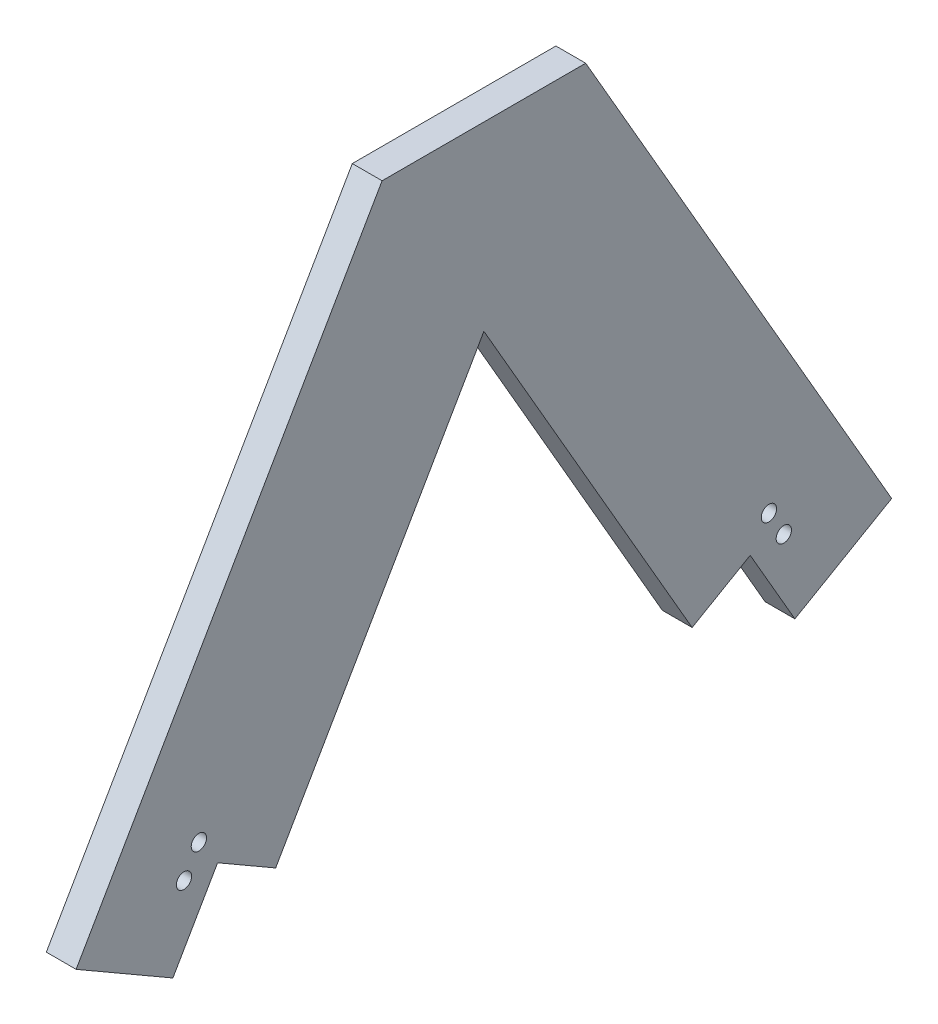
SolidWorks part; units mm, degrees
ref_plane "Front Plane" through (0, 0, 0) normal (0, 0, 1) x (1, 0, 0)
ref_plane "Top Plane" through (0, 0, 0) normal (0, 1, 0) x (1, 0, 0)
ref_plane "Right Plane" through (0, 0, 0) normal (1, 0, 0) x (0, 0, -1)
sketch "Sketch1" plane through (0, 0, 0) normal (1, 0, 0) x (0, 0, -1)
  line L0 (0, 0) -> (76.2, 131.9823)
  line L1 (119.5861, 131.9823) -> (195.7861, 0)
  line L2 (0, 0) -> (43.9941, 0)
  line L3 (43.9941, 0) -> (97.893, 93.3557)
  line L4 (97.893, 93.3557) -> (151.792, 0)
  line L5 (151.792, 0) -> (195.7861, 0)
  line L6 (76.2, 131.9823) -> (119.5861, 131.9823)
  dimension "D1" = 152.4
  dimension "D2" = 152.4
  dimension "D3" = 38.1
  dimension "D4" = 38.1
  dimension "D5" = 60
extrude "Boss-Extrude1" add sketch "Sketch1" along normal blind 6.35
sketch "Sketch2" plane through (6.35, 0, 0) normal (1, 0, 0) x (0, 0, -1)
  line L0 (43.9941, 0) -> (10.9985, 19.05)
  line L1 (76.2, 131.9823) -> (0, 0) construction
  line L2 (10.9985, 19.05) -> (0, 0)
  line L3 (0, 0) -> (43.9941, 0)
extrude "Cut-Extrude1" cut sketch "Sketch2" against normal through all
sketch "Sketch3" plane through (6.35, 0, 0) normal (1, 0, 0) x (0, 0, -1)
  line L0 (43.9941, 0) -> (31.6208, 7.1437)
  line L1 (43.9941, 0) -> (10.9985, 19.05) construction
  line L2 (31.6208, 7.1437) -> (41.1458, 23.6415)
  line L3 (41.1458, 23.6415) -> (53.5191, 16.4978)
  line L4 (43.9941, 0) -> (97.893, 93.3557) construction
  line L5 (53.5191, 16.4978) -> (43.9941, 0)
  dimension "D1" = 14.2875
  dimension "D2" = 19.05
extrude "Cut-Extrude2" cut sketch "Sketch3" against normal through all
sketch "Sketch4" plane through (6.35, 0, 0) normal (1, 0, 0) x (0, 0, -1)
  line L0 (151.792, 0) -> (184.7876, 19.05)
  line L1 (195.7861, 0) -> (119.5861, 131.9823) construction
  line L2 (184.7876, 19.05) -> (195.7861, 0)
  line L3 (195.7861, 0) -> (151.792, 0)
extrude "Cut-Extrude3" cut sketch "Sketch4" against normal through all
sketch "Sketch5" plane through (6.35, 0, 0) normal (1, 0, 0) x (0, 0, -1)
  line L0 (151.792, 0) -> (164.1653, 7.1437)
  line L1 (184.7876, 19.05) -> (151.792, 0) construction
  line L2 (164.1653, 7.1437) -> (154.6403, 23.6415)
  line L3 (154.6403, 23.6415) -> (142.267, 16.4978)
  line L4 (97.893, 93.3557) -> (151.792, 0) construction
  line L5 (142.267, 16.4978) -> (151.792, 0)
  dimension "D1" = 19.05
  dimension "D2" = 14.2875
extrude "Cut-Extrude4" cut sketch "Sketch5" against normal through all
hole_wizard "CSK for #4 Flat Head Machine Screw1" positions "Sketch7" profile "Sketch6" countersink size "#4" standard "ANSI Inch" end condition through all
sketch "Sketch7" plane through (0, 0, 0) normal (-1, 0, 0) x (0, 0, 1)
  point P0 (-161.8031, 23.9352)
sketch "Sketch6" plane through (0, 23.9352, -161.8031) normal (0, 1, 0) x (0, 0, 1)
  line L0 (0, 0) -> (0, 6.35)
  line L1 (0, 6.35) -> (1.6319, 6.35)
  line L2 (1.6319, 6.35) -> (1.6319, 1.4098)
  line L3 (1.6319, 1.4098) -> (2.8575, 0)
  line L5 (2.8575, 0) -> (0, 0)
  line L6 (-1.6319, 1.4098) -> (-2.8575, 0) construction
  line L11 (0, -6.35) -> (0, 107.95) construction
  dimension "Thru Hole Dia." = 3.2639
  dimension "Thru Hole Depth" = 6.35
  dimension "Near C'Sink Dia." = 5.715
  dimension "Near C'Sink Angle" = 82
hole_wizard "CSK for #4 Flat Head Machine Screw2" positions "Sketch9" profile "Sketch8" countersink size "#4" standard "ANSI Inch" end condition through all
sketch "Sketch9" plane through (0, 0, 0) normal (-1, 0, 0) x (0, 0, 1)
  point P0 (-158.6281, 29.4344)
sketch "Sketch8" plane through (0, 29.4344, -158.6281) normal (0, 1, 0) x (0, 0, 1)
  line L0 (0, 0) -> (0, 6.35)
  line L1 (0, 6.35) -> (1.6319, 6.35)
  line L2 (1.6319, 6.35) -> (1.6319, 1.4098)
  line L3 (1.6319, 1.4098) -> (2.8575, 0)
  line L5 (2.8575, 0) -> (0, 0)
  line L6 (-1.6319, 1.4098) -> (-2.8575, 0) construction
  line L11 (0, -6.35) -> (0, 107.95) construction
  dimension "Thru Hole Dia." = 3.2639
  dimension "Thru Hole Depth" = 6.35
  dimension "Near C'Sink Dia." = 5.715
  dimension "Near C'Sink Angle" = 82
hole_wizard "CSK for #4 Flat Head Machine Screw3" positions "Sketch11" profile "Sketch10" countersink size "#4" standard "ANSI Inch" end condition through all
sketch "Sketch11" plane through (0, 0, 0) normal (-1, 0, 0) x (0, 0, 1)
  point P0 (-37.1579, 29.4344)
  point P3 (-33.9829, 23.9352)
sketch "Sketch10" plane through (0, 29.4344, -37.1579) normal (0, 1, 0) x (0, 0, 1)
  line L0 (0, 0) -> (0, 6.35)
  line L1 (0, 6.35) -> (1.6319, 6.35)
  line L2 (1.6319, 6.35) -> (1.6319, 1.4098)
  line L3 (1.6319, 1.4098) -> (2.8575, 0)
  line L5 (2.8575, 0) -> (0, 0)
  line L6 (-1.6319, 1.4098) -> (-2.8575, 0) construction
  line L11 (0, -6.35) -> (0, 107.95) construction
  dimension "Thru Hole Dia." = 3.2639
  dimension "Thru Hole Depth" = 6.35
  dimension "Near C'Sink Dia." = 5.715
  dimension "Near C'Sink Angle" = 82
